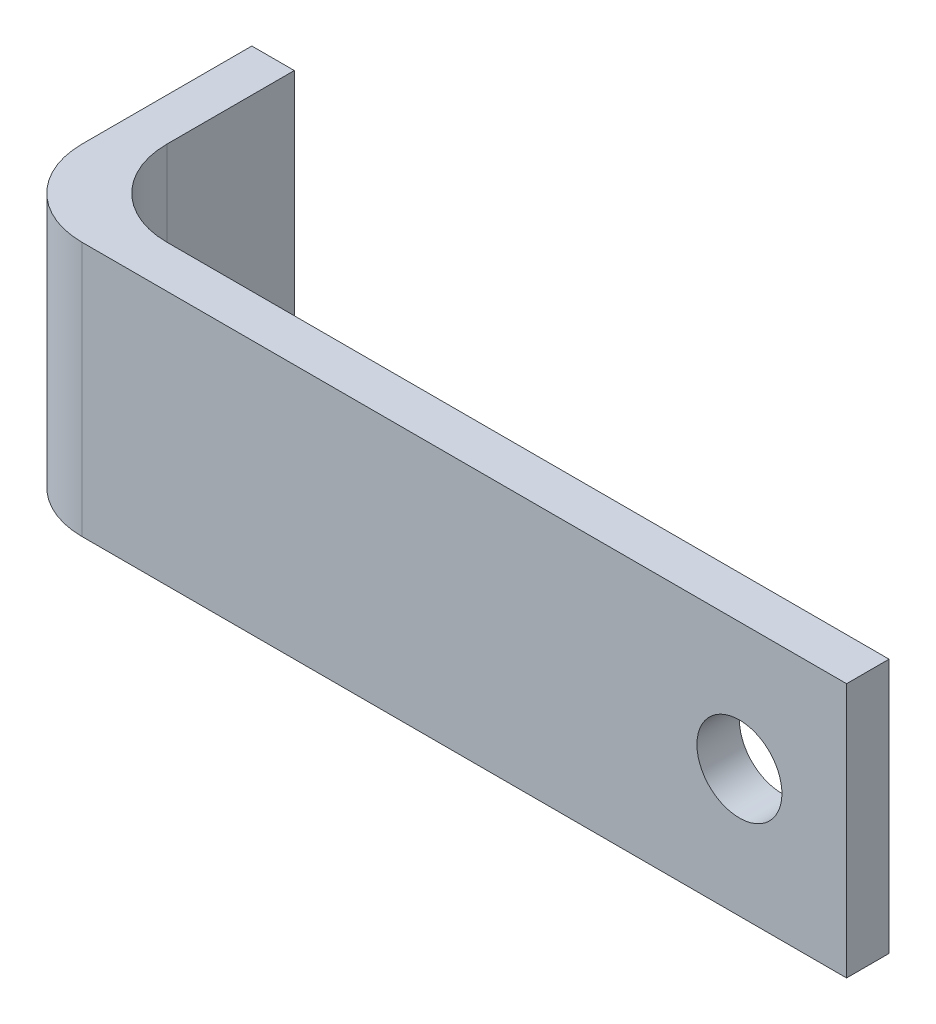
SolidWorks part; units mm, degrees
material "AISI 1020"
ref_plane "Front Plane" through (0, 0, 0) normal (0, 0, 1) x (1, 0, 0)
ref_plane "Top Plane" through (0, 0, 0) normal (0, 1, 0) x (1, 0, 0)
ref_plane "Right Plane" through (0, 0, 0) normal (1, 0, 0) x (0, 0, -1)
sketch "Sketch1" plane through (0, 0, 0) normal (0, 1, 0) x (1, 0, 0)
  line L0 (-57.3474, 10.3991) -> (-52.3474, 10.3991)
  line L1 (-52.3474, 10.3991) -> (-52.3474, -4.6009)
  line L2 (-42.3474, -14.6009) -> (42.6526, -14.6009)
  line L3 (42.6526, -14.6009) -> (42.6526, -19.6009)
  line L4 (42.6526, -19.6009) -> (-47.3474, -19.6009)
  line L5 (-57.3474, -9.6009) -> (-57.3474, 10.3991)
  arc A0 (-52.3474, -4.6009) -> (-42.3474, -14.6009) centre (-42.3474, -4.6009) ccw
  arc A1 (-57.3474, -9.6009) -> (-47.3474, -19.6009) centre (-47.3474, -9.6009) ccw
  point P8 (-52.3474, -14.6009)
  point P11 (-57.3474, -19.6009)
  dimension "D6" = 10
  dimension "D1" = 100
  dimension "D2" = 5
  dimension "D3" = 5
  dimension "D4" = 95
  dimension "D5" = 25
extrude "Boss-Extrude1" add sketch "Sketch1" along normal mid plane 30
sketch "Sketch2" plane through (0, 0, 14.6009) normal (0, 0, -1) x (-1, 0, 0)
  circle A0 centre (-30.0408, 0) radius 5
extrude "Cut-Extrude1" cut sketch "Sketch2" against normal blind 30
sketch "Sketch3" plane through (-57.3474, 0, 0) normal (-1, 0, 0) x (0, 0, 1)
  circle A0 centre (0, 0) radius 2.5
extrude "Boss-Extrude2" add sketch "Sketch3" along normal blind 1
